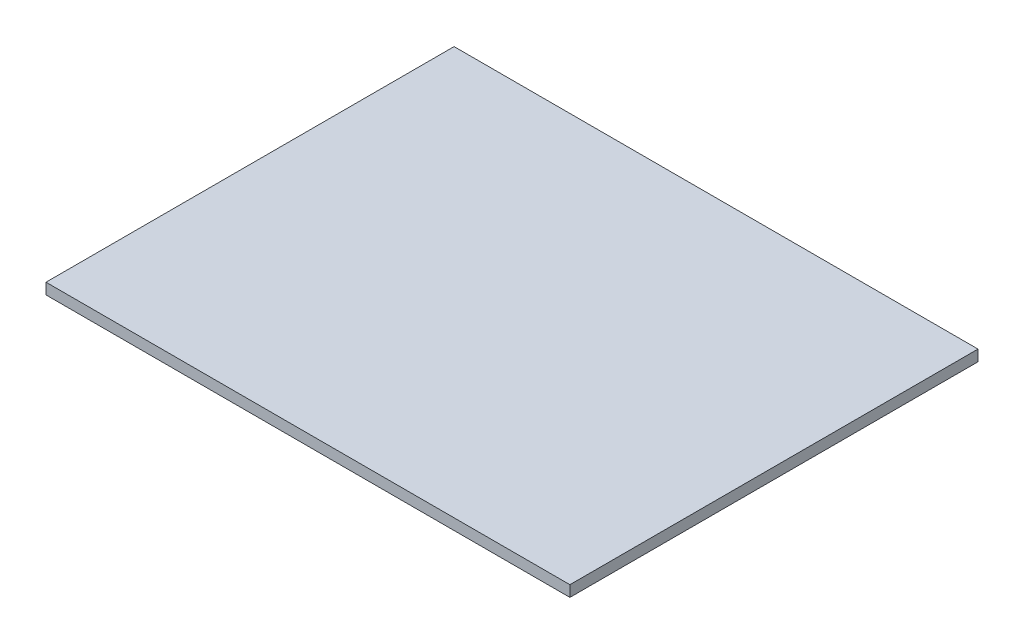
SolidWorks part; units mm, degrees
ref_plane "Front Plane" through (0, 0, 0) normal (0, 0, 1) x (1, 0, 0)
ref_plane "Top Plane" through (0, 0, 0) normal (0, 1, 0) x (1, 0, 0)
ref_plane "Right Plane" through (0, 0, 0) normal (1, 0, 0) x (0, 0, -1)
sketch "Sketch1" plane through (0, 0, 0) normal (0, 1, 0) x (1, 0, 0)
  line L1 (-237.5, 185) -> (237.5, 185)
  line L2 (-237.5, 185) -> (-237.5, -185)
  line L3 (-237.5, -185) -> (237.5, -185)
  line L4 (237.5, 185) -> (237.5, -185)
  line L5 (-237.5, 185) -> (237.5, -185) construction
  line L6 (-237.5, -185) -> (237.5, 185) construction
  point P0 (0, 0)
  dimension "D1" = 475
  dimension "D2" = 370
extrude "Boss-Extrude1" add sketch "Sketch1" along normal blind 10
